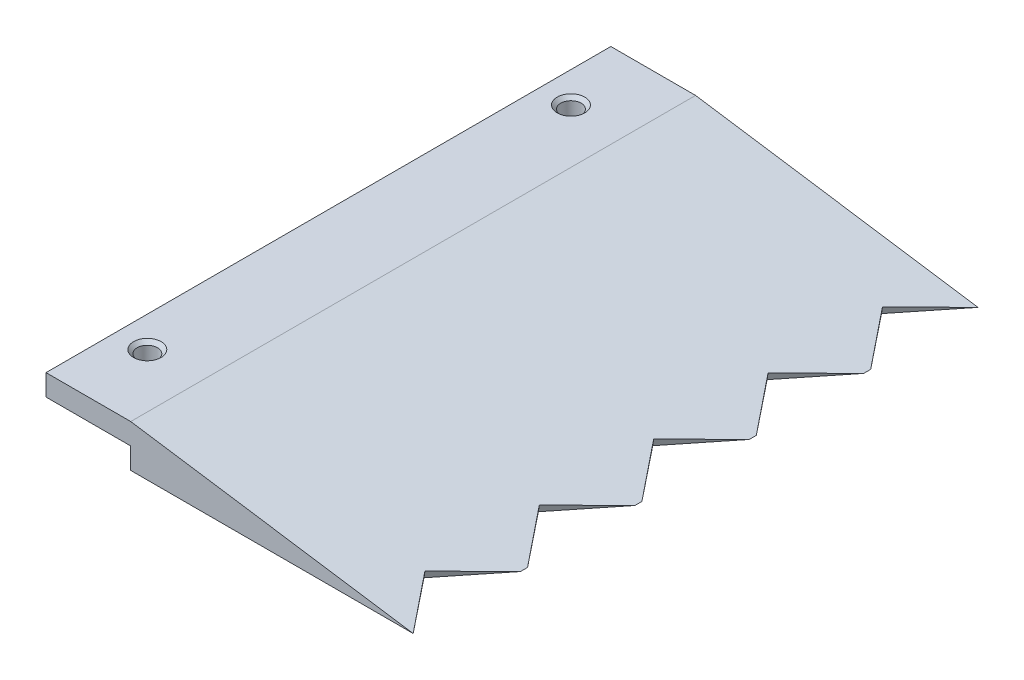
SolidWorks part; units mm, degrees
ref_plane "Front Plane" through (0, 0, 0) normal (0, 0, 1) x (1, 0, 0)
ref_plane "Top Plane" through (0, 0, 0) normal (0, 1, 0) x (1, 0, 0)
ref_plane "Right Plane" through (0, 0, 0) normal (1, 0, 0) x (0, 0, -1)
sketch "Sketch1" plane through (0, 0, 0) normal (0, 0, 1) x (1, 0, 0)
  line L0 (0, 6) -> (12, 6)
  line L1 (0, -55) -> (0, 55) construction
  line L2 (12, 6) -> (52, 0)
  line L3 (55, 0) -> (-55, 0) construction
  line L4 (52, 0) -> (12, 0)
  line L5 (12, 0) -> (12, 3)
  line L6 (12, 3) -> (0, 3)
  line L7 (0, 3) -> (0, 6)
  dimension "D1" = 40
  dimension "D2" = 3
  dimension "D3" = 3
  dimension "D4" = 12
extrude "Boss-Extrude1" add sketch "Sketch1" along normal mid plane 80
sketch "Sketch3" plane through (1.1443, 7.6284, 0) normal (0.1483, 0.9889, 0) x (0.9889, -0.1483, 0)
  line L15 (51.4247, -40) -> (45.4247, -32.4)
  line L16 (45.4247, -32.4) -> (51.4247, -24.8)
  line L17 (51.4247, -40) -> (51.4247, 40) construction
  line L18 (51.4247, -40) -> (51.4247, -24.8)
  line L25 (51.4247, -23.8) -> (51.4247, -8.6)
  line L26 (45.4247, -16.2) -> (51.4247, -8.6)
  line L27 (51.4247, -23.8) -> (45.4247, -16.2)
  line L28 (51.4247, -7.6) -> (51.4247, 7.6)
  line L29 (45.4247, 0) -> (51.4247, 7.6)
  line L30 (51.4247, -7.6) -> (45.4247, 0)
  line L31 (51.4247, 8.6) -> (51.4247, 23.8)
  line L32 (45.4247, 16.2) -> (51.4247, 23.8)
  line L33 (51.4247, 8.6) -> (45.4247, 16.2)
  line L34 (51.4247, 24.8) -> (51.4247, 40)
  line L35 (45.4247, 32.4) -> (51.4247, 40)
  line L36 (51.4247, 24.8) -> (45.4247, 32.4)
  dimension "D1" = 15.2
  dimension "D2" = 6
  dimension "D3" = 1
  dimension "D7" = 5
extrude "Cut-Extrude1" cut sketch "Sketch3" against normal mid plane 80
sketch "Sketch4" plane through (0, 6, 0) normal (0, 1, 0) x (1, 0, 0)
  line L0 (12, -40) -> (0, -40) construction
  line L1 (12, -40) -> (12, 40) construction
  line L2 (12, 40) -> (0, 40) construction
  circle A0 centre (4.35, -30) radius 1.45
  circle A1 centre (4.35, 30) radius 1.45
  dimension "D1" = 2.9
  dimension "D2" = 10
  dimension "D3" = 7.65
  dimension "D5" = 10
  dimension "D4" = 2
extrude "Cut-Extrude2" cut sketch "Sketch4" against normal mid plane 80
chamfer "Chamfer1" distance 0.5 angle 45 2 edges at (4.35, 6, 28.55) (4.35, 6, -31.45)
